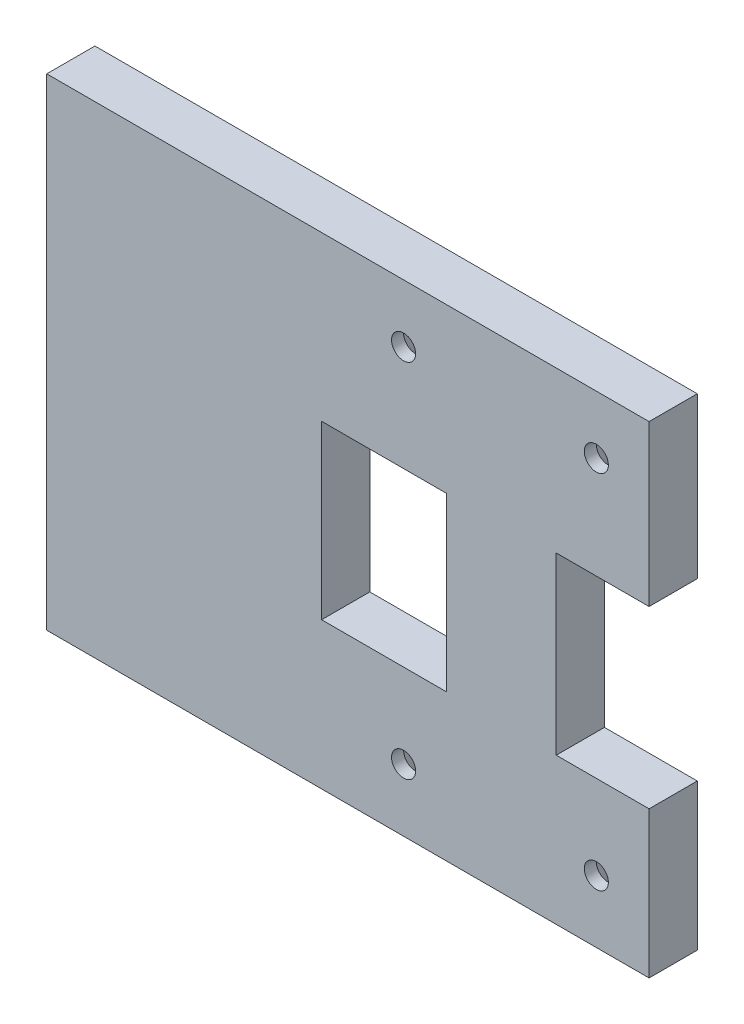
SolidWorks part; units mm, degrees
ref_plane "Front Plane" through (0, 0, 0) normal (0, 0, 1) x (1, 0, 0)
ref_plane "Top Plane" through (0, 0, 0) normal (0, 1, 0) x (1, 0, 0)
ref_plane "Right Plane" through (0, 0, 0) normal (1, 0, 0) x (0, 0, -1)
ref_plane "Plane1" through (0, 0, 34.8116) normal (0, 0, -1) x (-1, 0, 0)
sketch "Sketch1" plane through (0, 0, 34.8116) normal (0, 0, -1) x (-1, 0, 0)
  line L0 (-23.5355, 118.8347) -> (-23.5355, 78.8347)
  line L1 (-23.5355, 78.8347) -> (26.4645, 78.8347)
  line L2 (26.4645, 78.8347) -> (26.4645, 118.8347)
  line L3 (26.4645, 118.8347) -> (-23.5355, 118.8347)
extrude "Boss-Extrude1" add sketch "Sketch1" against normal blind 4
sketch "Sketch2" plane through (0, 0, 38.8116) normal (0, 0, 1) x (1, 0, 0)
  line L0 (23.5355, 90.9981) -> (23.5355, 105.5372)
  line L1 (23.5355, 105.5372) -> (15.8296, 105.5372)
  line L2 (15.8296, 105.5372) -> (15.8296, 90.9981)
  line L3 (15.8296, 90.9981) -> (23.5355, 90.9981)
extrude "Cut-Extrude1" cut sketch "Sketch2" against normal through all
sketch "Sketch3" plane through (0, 0, 38.8116) normal (0, 0, 1) x (1, 0, 0)
  line L0 (6.7257, 105.2654) -> (-3.6465, 105.2654)
  line L1 (-3.6465, 105.2654) -> (-3.6465, 90.9981)
  line L2 (-3.6465, 90.9981) -> (6.7257, 90.9981)
  line L3 (6.7257, 90.9981) -> (6.7257, 105.2654)
extrude "Cut-Extrude2" cut sketch "Sketch3" against normal through all
hole_wizard "Ø2.0 (2) Diameter Hole1" positions "Sketch5" profile "Sketch4" hole size "Ø2.0" standard "ANSI Metric"
sketch "Sketch5" plane through (0, 0, 34.8116) normal (0, 0, -1) x (-1, 0, 0)
  point P0 (-3.1566, 84.0163)
  point P1 (-19.1566, 84.0163)
  point P2 (-19.1566, 114.0163)
  point P3 (-3.1566, 114.0163)
sketch "Sketch4" plane through (3.1566, 84.0163, 34.8116) normal (1, 0, 0) x (0, 1, 0)
  line L0 (0, 0) -> (0, 4)
  line L1 (0, 4) -> (1, 4)
  line L2 (1, 4) -> (1, 3)
  line L3 (1, 3) -> (4, 0)
  line L5 (4, 0) -> (0, 0)
  line L6 (-1, 3) -> (-4, 0) construction
  line L11 (0, -6.35) -> (0, 107.95) construction
  dimension "Thru Hole Dia." = 2
  dimension "Thru Hole Depth" = 4
  dimension "Near C'Sink Dia." = 8
  dimension "Near C'Sink Angle" = 90
